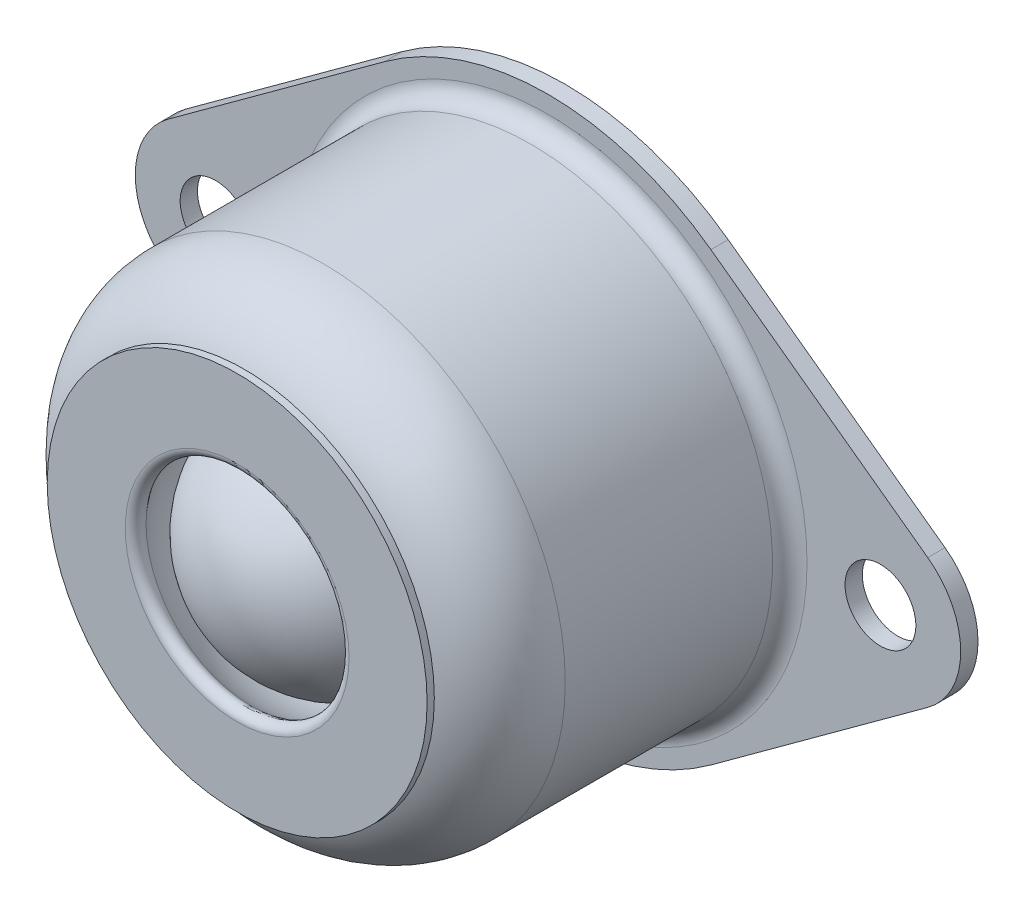
SolidWorks part; units mm, degrees
ref_plane "Front" through (0, 0, 0) normal (0, 0, 1) x (1, 0, 0)
ref_plane "Top" through (0, 0, 0) normal (0, 1, 0) x (1, 0, 0)
ref_plane "Right" through (0, 0, 0) normal (1, 0, 0) x (0, 0, -1)
sketch "Sketch1" plane through (0, 0, 0) normal (0, 0, 1) x (1, 0, 0)
  circle A0 centre (0, 0) radius 14
  circle A1 centre (0, 0) radius 8
  dimension "D1" = 28
  dimension "D2" = 16
extrude "Boss-Extrude1" add sketch "Sketch1" along normal blind 19
sketch "Sketch2" plane through (0, 0, 0) normal (0, 0, -1) x (-1, 0, 0)
  line L0 (-19.25, 0) -> (-19.25, 11.0091) construction
  line L1 (21.9917, 3.7557) -> (9.4338, 12.923)
  line L2 (-21.9917, 3.7557) -> (-9.4338, 12.923)
  line L3 (0, 0) -> (0, 11.4116) construction
  line L4 (0, 0) -> (-19.25, 0) construction
  line L5 (0, 0) -> (11.6431, 0) construction
  line L6 (-21.3, 0) -> (-23.9, 0) construction
  line L7 (21.9917, -3.7557) -> (9.4338, -12.923)
  line L8 (-21.9917, -3.7557) -> (-9.4338, -12.923)
  arc A0 (-21.9917, 3.7557) -> (-21.9917, -3.7557) centre (-19.25, 0) ccw
  circle A2 centre (-19.25, 0) radius 2.05
  circle A9 centre (0, 0) radius 12.5
  arc A10 (9.4338, 12.923) -> (-9.4338, 12.923) centre (0, 0) ccw
  circle A11 centre (19.25, 0) radius 2.05
  arc A12 (21.9917, 3.7557) -> (21.9917, -3.7557) centre (19.25, 0) cw
  arc A13 (9.4338, -12.923) -> (-9.4338, -12.923) centre (0, 0) cw
  point P21 (-10.0918, 0.077)
  dimension "D3" = 2.6
  dimension "D4" = 16
  dimension "D5" = 25
  dimension "D2" = 4.1
  dimension "D1" = 19.25
extrude "Boss-Extrude2" add sketch "Sketch2" against normal blind 1
sketch "Sketch6" plane through (0, 0, 0) normal (0, 1, 0) x (1, 0, 0)
  line L0 (0, -20) -> (-21.092, -20) construction
  line L1 (0, -6) -> (0, -20)
  line L2 (-21.9917, 0) -> (-9.4338, 0) construction
  arc A0 (0, -20) -> (0, -6) centre (0, -13) ccw
  dimension "D1" = 14
  dimension "D2" = 20
revolve "Revolve1" add sketch "Sketch6" angle 360 about L1
fillet "Fillet1" radius 1 1 edges at (-14, 0, 1)
fillet "Fillet2" radius 5 1 edges at (14, 0, 19)
sketch "Sketch8" plane through (0, 0, 0) normal (0, 0, -1) x (-1, 0, 0)
  circle A0 centre (0, 0) radius 12.5
  dimension "D1" = 25
extrude "Cut-Extrude2" cut sketch "Sketch8" against normal blind 8.8
sketch "Sketch7" plane through (0, 0, 0) normal (0, 1, 0) x (1, 0, 0)
  line L1 (0, -2) -> (0, -21) construction
  line L2 (9.4338, 0) -> (-9.4338, 0) construction
  line L4 (5.2915, -19) -> (11, -19)
  line L6 (-9, -19) -> (9, -19) construction
  line L7 (11, -19) -> (11, -13)
  line L9 (0, -5) -> (0, -21) construction
  line L10 (-3, -2.417) -> (-3, -23.583) construction
  line L11 (0, -2) -> (0, -5)
  arc A2 (5.2915, -19) -> (0, -5) centre (0, -13) ccw
  arc A3 (11, -13) -> (0, -2) centre (0, -13) ccw
  arc A4 (-3, -23.583) -> (-3, -2.417) centre (0, -13) ccw construction
  arc A5 (0, -21) -> (0, -5) centre (0, -13) ccw construction
  dimension "D3" = 3
  dimension "D1" = 13
  dimension "D2" = 16
revolve "Revolve2" add sketch "Sketch7" angle 360 about L1
fillet "Fillet3" radius 0.5 1 edges at (-5.2915, 0, 19)
fillet "Fillet4" radius 1 2 edges at (-10.1666, 0, 8.8) (-12.5, 0, 8.8)
fillet "Fillet5" radius 2 1 edges at (-12.5, 0, 0)
